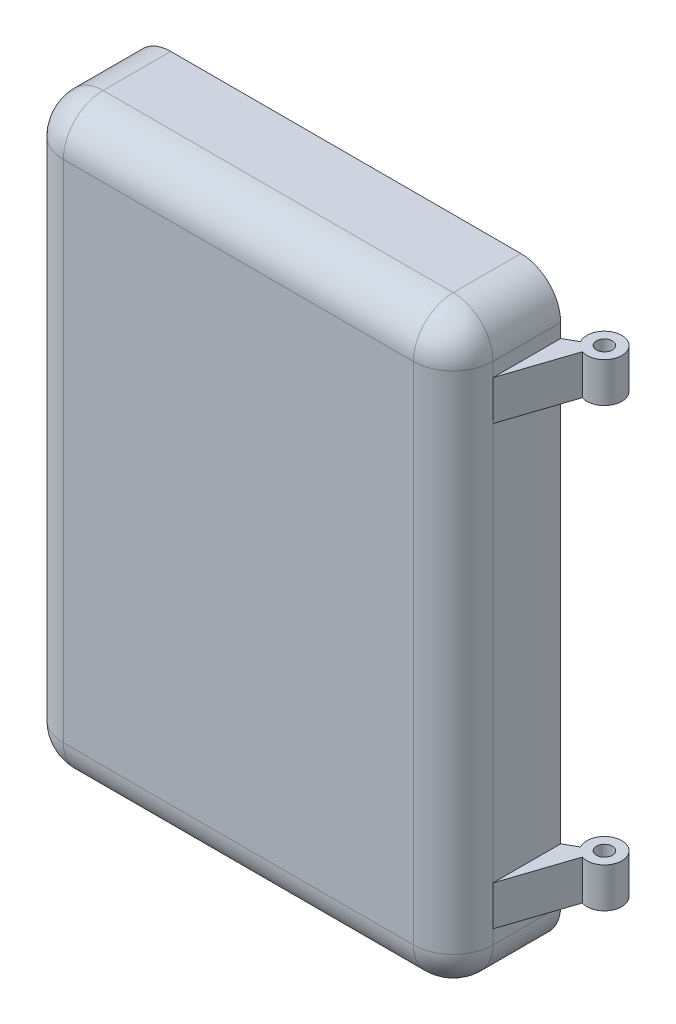
SolidWorks part; units mm, degrees
ref_plane "Front Plane" through (0, 0, 0) normal (0, 0, 1) x (1, 0, 0)
ref_plane "Top Plane" through (0, 0, 0) normal (0, 1, 0) x (1, 0, 0)
ref_plane "Right Plane" through (0, 0, 0) normal (1, 0, 0) x (0, 0, -1)
sketch "Sketch1" plane through (0, 0, 0) normal (0, 0, 1) x (1, 0, 0)
  line L1 (54, 73.5) -> (-54, 73.5)
  line L2 (54, 73.5) -> (54, -73.5)
  line L3 (54, -73.5) -> (-54, -73.5)
  line L4 (-54, 73.5) -> (-54, -73.5)
  line L5 (54, 73.5) -> (-54, -73.5) construction
  line L6 (54, -73.5) -> (-54, 73.5) construction
  point P0 (0, 0)
  dimension "D1" = 147
  dimension "D2" = 108
ref_plane "Plane1" through (0, 0, 27) normal (0, 0, 1) x (1, 0, 0)
sketch "Sketch2" plane through (0, 0, 27) normal (0, 0, 1) x (1, 0, 0)
  line L1 (-54, 73.5) -> (54, 73.5)
  line L2 (-54, 73.5) -> (-54, -73.5)
  line L3 (-54, -73.5) -> (54, -73.5)
  line L4 (54, 73.5) -> (54, -73.5)
  line L5 (-54, 73.5) -> (54, -73.5) construction
  line L6 (-54, -73.5) -> (54, 73.5) construction
  point P0 (0, 0)
  dimension "D1" = 147
  dimension "D2" = 108
loft "Loft1" add profiles "Sketch2", "Sketch1"
fillet "Fillet1" radius 10 8 edges
shell "Shell1" thickness 2.7
ref_plane "Plane2" through (0, 50, 0) normal (0, 1, 0) x (1, 0, 0)
sketch "Sketch4" plane through (0, 50, 0) normal (0, 1, 0) x (1, 0, 0)
  line L0 (54, 0) -> (54, -17) construction
  line L1 (54, 0) -> (54, -17)
  line L2 (54, -17) -> (59.6139, -0.1582)
  line L3 (57.1943, 1.8253) -> (54, 0)
  circle A0 centre (61, 4) radius 4.3832
  circle A1 centre (61, 4) radius 2
  dimension "D1" = 4
extrude "Boss-Extrude1" add sketch "Sketch4" along normal blind 10
mirror "Mirror1" about plane through (0, 0, 0) normal (0, 1, 0) of "Boss-Extrude1"
